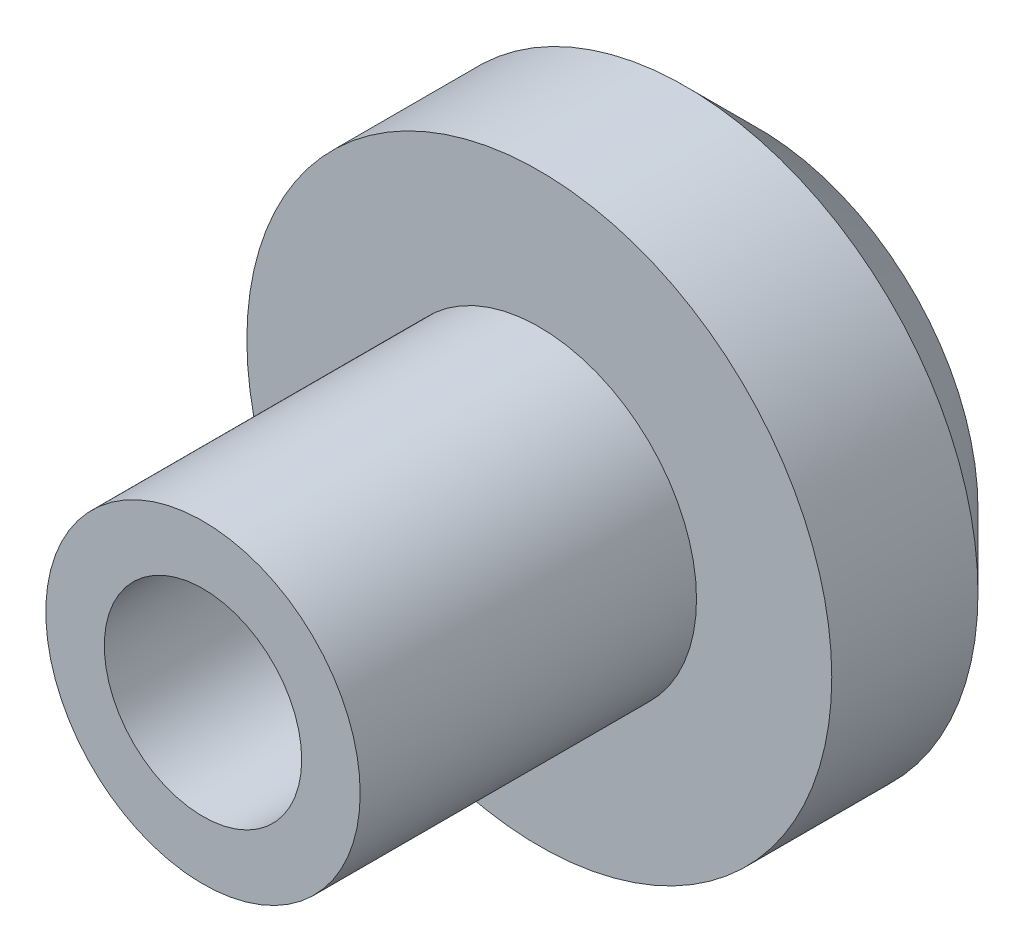
SolidWorks part; units mm, degrees
material "Copper"
ref_plane "Front Plane" through (0, 0, 0) normal (0, 0, 1) x (1, 0, 0)
ref_plane "Top Plane" through (0, 0, 0) normal (0, 1, 0) x (1, 0, 0)
ref_plane "Right Plane" through (0, 0, 0) normal (1, 0, 0) x (0, 0, -1)
sketch "Sketch1" plane through (0, 0, 0) normal (0, 0, 1) x (1, 0, 0)
  circle A0 centre (0, 0) radius 4
  dimension "D1" = 8
extrude "Boss-Extrude1" add sketch "Sketch1" along normal blind 3
sketch "Sketch2" plane through (0, 0, 3) normal (0, 0, 1) x (1, 0, 0)
  circle A0 centre (0, 0) radius 2.15
  dimension "D1" = 4.3
extrude "Boss-Extrude2" add sketch "Sketch2" along normal blind 4.6
sketch "Sketch3" plane through (0, 0, 7.6) normal (0, 0, 1) x (1, 0, 0)
  circle A0 centre (0, 0) radius 1.35
  dimension "D1" = 2.7
extrude "Cut-Extrude1" cut sketch "Sketch3" against normal through all
chamfer "Chamfer1" distance 1 angle 45 1 edges at (4, 0, 0)
